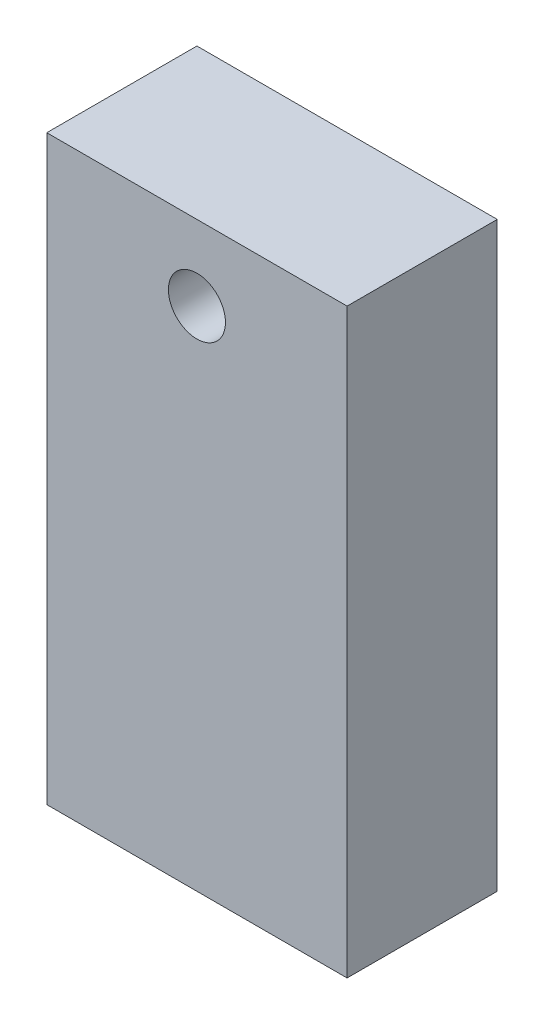
SolidWorks part; units mm, degrees
ref_plane "Front Plane" through (0, 0, 0) normal (0, 0, 1) x (1, 0, 0)
ref_plane "Top Plane" through (0, 0, 0) normal (0, 1, 0) x (1, 0, 0)
ref_plane "Right Plane" through (0, 0, 0) normal (1, 0, 0) x (0, 0, -1)
sketch "Sketch2" plane through (0, 0, 0) normal (0, 1, 0) x (1, 0, 0)
  line L1 (0, 0) -> (50.8, 0)
  line L2 (0, 0) -> (0, 25.4)
  line L3 (0, 25.4) -> (50.8, 25.4)
  line L4 (50.8, 0) -> (50.8, 25.4)
  dimension "D1" = 25.4
  dimension "D2" = 50.8
extrude "Boss-Extrude1" add sketch "Sketch2" along normal blind 98.425
sketch "Sketch3" plane through (0, 0, 0) normal (0, 0, 1) x (1, 0, 0)
  line L0 (0, 98.425) -> (50.8, 98.425) construction
  circle A0 centre (25.4, 85.725) radius 4.826
  dimension "D2" = 9.652
  dimension "D1" = 12.7
extrude "Cut-Extrude1" cut sketch "Sketch3" against normal through all
